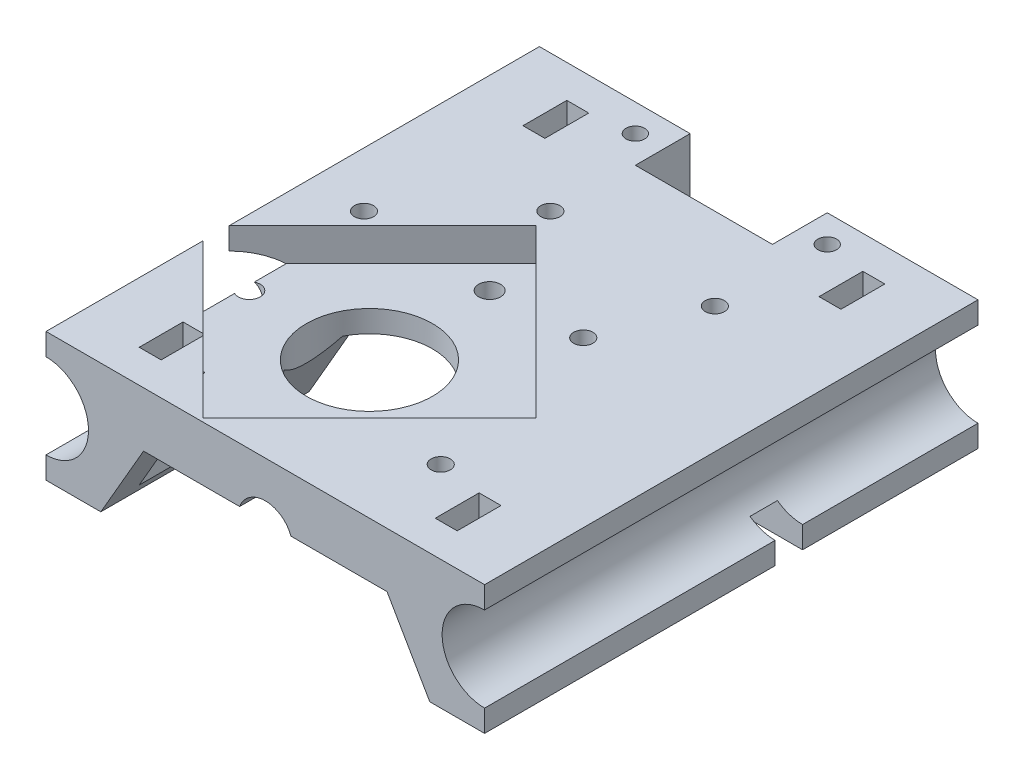
SolidWorks part; units mm, degrees
material "ABS"
ref_plane "Plano frontal" through (0, 0, 0) normal (0, 0, 1) x (1, 0, 0)
ref_plane "Plano superior" through (0, 0, 0) normal (0, 1, 0) x (1, 0, 0)
ref_plane "Plano direito" through (0, 0, 0) normal (1, 0, 0) x (0, 0, -1)
sketch "Esboço1" plane through (0, 0, 0) normal (0, 0, 1) x (1, 0, 0)
  line L0 (40, 0) -> (-40, 0)
  line L1 (-40, -19.5) -> (-40, -23.5)
  line L2 (-40, -23.5) -> (-30, -23.5)
  line L3 (-30, -23.5) -> (-22.2058, -10)
  line L4 (-22.2058, -10) -> (-4.6837, -10)
  line L5 (-40, 0) -> (-40, -4)
  line L6 (0, 0) -> (0, -46.1263) construction
  line L7 (40, 0) -> (40, -4)
  line L8 (30, -23.5) -> (22.2058, -10)
  line L9 (40, -23.5) -> (30, -23.5)
  line L10 (40, -19.5) -> (40, -23.5)
  line L11 (4.6837, -10) -> (22.2058, -10)
  line L12 (-40, -11.75) -> (40, -11.75) construction
  arc A0 (-40, -4) -> (-40, -19.5) centre (-40, -11.75) cw
  arc A1 (40, -4) -> (40, -19.5) centre (40, -11.75) ccw
  arc A2 (4.6837, -10) -> (-4.6837, -10) centre (0, -11.75) ccw
  point P17 (0, -12.2866)
  point P21 (0, 0)
  dimension "D1" = 7.75
  dimension "D7" = 5
  dimension "D2" = 4
  dimension "D3" = 60
  dimension "D4" = 10
  dimension "D5" = 10
  dimension "D6" = 40
extrude "Ressalto-extrusão1" add sketch "Esboço1" along normal blind 90
sketch "Esboço2" plane through (0, 0, 0) normal (0, 1, 0) x (1, 0, 0)
  line L1 (-42.4056, -59) -> (-12, -28.5944)
  line L2 (-42.4056, -59) -> (-12, -89.4056)
  line L3 (-12, -89.4056) -> (18.4056, -59)
  line L4 (-12, -28.5944) -> (18.4056, -59)
  line L5 (-42.4056, -59) -> (18.4056, -59) construction
  line L6 (-12, -89.4056) -> (-12, -28.5944) construction
  line L8 (-40, -90) -> (-40, 0) construction
  line L9 (40, -90) -> (-40, -90) construction
  line L11 (-22.2058, -90) -> (-4.6837, -90) construction
  circle A0 centre (-12, -59) radius 5
  point P0 (-12, -59)
  dimension "D4" = 10
  dimension "D1" = 43
  dimension "D2" = 28
  dimension "D3" = 31
extrude "Corte-extrusão1" cut sketch "Esboço2" against normal offset from surface (6 mm away) 4 up to face at (-13.4448, -10, 45)
sketch "Esboço3" plane through (0, -6, 0) normal (0, 1, 0) x (1, 0, 0)
  line L2 (-6.7523, -61.9088) -> (5.6269, -39.576) construction
  line L3 (-17.6288, -61.0776) -> (-25.3093, -40.2687) construction
  line L4 (-12, -37.0797) -> (9.9203, -59) construction
  line L5 (-12, -37.0797) -> (-33.9203, -59) construction
  line L6 (-33.9203, -59) -> (-12, -80.9203) construction
  line L7 (9.9203, -59) -> (-12, -80.9203) construction
  line L8 (-12, -37.0797) -> (-12, -80.9203) construction
  line L9 (-33.9203, -59) -> (9.9203, -59) construction
  line L10 (40, -90) -> (-40, -90) construction
  line L13 (-12, -28.5944) -> (-40, -56.5944) construction
  line L14 (4.6837, -90) -> (22.2058, -90) construction
  line L16 (-12.5, -10) -> (12.5, -10)
  line L17 (-12.5, -10) -> (-12.5, 0)
  line L18 (-12.5, 0) -> (12.5, 0)
  line L19 (12.5, -10) -> (12.5, 0)
  line L20 (-12.5, -10) -> (12.5, 0) construction
  line L21 (-12.5, 0) -> (12.5, -10) construction
  line L22 (0, -12.8859) -> (0, -1.9558) construction
  line L24 (18.4056, -59) -> (-12, -28.5944) construction
  circle A0 centre (-12, -37.0797) radius 2
  circle A1 centre (9.9203, -59) radius 2
  circle A2 centre (-12, -80.9203) radius 2
  circle A3 centre (-33.9203, -59) radius 2
  circle A4 centre (-12, -59) radius 11.5
  arc A5 (-17.6288, -61.0776) -> (-6.7523, -61.9088) centre (-12, -59) ccw construction
  circle A6 centre (-30, -42) radius 1.75
  circle A7 centre (10, -42) radius 1.75
  circle A8 centre (10, -42) radius 5 construction
  circle A9 centre (-30, -42) radius 5 construction
  circle A10 centre (-17.5, -5) radius 1.7
  circle A11 centre (17.5, -5) radius 1.7
  circle A12 centre (17, -75) radius 1.75
  circle A13 centre (-13, -25) radius 1.75
  circle A14 centre (17, -25) radius 1.75
  circle A15 centre (17, -25) radius 7.5 construction
  circle A16 centre (-13, -25) radius 7.5 construction
  circle A17 centre (17, -75) radius 7.5 construction
  point P0 (-11.5, -62)
  point P5 (0, 0)
  point P6 (-12, -59)
  point P29 (0, 0)
  point P38 (0, -5)
  point P60 (17, -75)
  point P66 (12.5, -5)
  dimension "D3" = 23
  dimension "D4" = 12
  dimension "D5" = 3.5
  dimension "D8" = 10
  dimension "D12" = 3.4
  dimension "D13" = 3.5
  dimension "D17" = 15
  dimension "D19" = 4
  dimension "D2" = 31
  dimension "D6" = 48
  dimension "D7" = 40
  dimension "D9" = 10
  dimension "D10" = 25
  dimension "D11" = 17.5
  dimension "D14" = 15
  dimension "D15" = 30
  dimension "D16" = 50
  dimension "D18" = 22
  dimension "D20" = 17
  dimension "D21" = 31
  dimension "D22" = 7
  dimension "D23" = 17
extrude "Corte-extrusão2" cut sketch "Esboço3" against normal through all and the other way through all
sketch "Esboço4" plane through (0, -10, 0) normal (0, -1, 0) x (1, 0, 0)
  line L0 (-44.5112, 37) -> (44.1077, 37)
  line L2 (-44.5112, 37) -> (-44.5112, 32)
  line L3 (-44.5112, 32) -> (44.1077, 32)
  line L4 (44.1077, 32) -> (44.1077, 37)
  circle A0 centre (-30, 42) radius 5 construction
  circle A1 centre (10, 42) radius 5 construction
  point P11 (-28.4465, 37.2475)
  dimension "D1" = 10
  dimension "D2" = 5
extrude "Corte-extrusão4" cut sketch "Esboço4" against normal blind 12 from offset 20
sketch "Esboço6" plane through (0, -23.5, 0) normal (0, -1, 0) x (1, 0, 0)
  line L0 (-40, 90) -> (-40, 37) construction
  line L2 (-20, 32) -> (-40, 32)
  line L5 (-20, 32) -> (-20, 52)
  line L6 (-20, 52) -> (-40, 52)
  line L7 (-40, 32) -> (-40, 52)
  line L8 (-20, 32) -> (-40, 52) construction
  line L9 (-20, 52) -> (-40, 32) construction
  line L10 (-30, 32) -> (-40, 32) construction
  circle A0 centre (17, 75) radius 8
  circle A1 centre (17, 25) radius 8
  circle A2 centre (-13, 25) radius 8
  point P0 (-30, 42)
  dimension "D1" = 16
extrude "Corte-extrusão7" cut sketch "Esboço6" against normal up to surface (13.5 mm away) up to face at (-14, -10, 80.9203)
sketch "Esboço7" plane through (0, 0, 0) normal (0, 1, 0) x (1, 0, 0)
  line L0 (-32.25, 0) -> (-32.25, -90) construction
  line L1 (40, -90) -> (-40, -90) construction
  line L3 (32.25, -90) -> (32.25, 0) construction
  line L5 (27.0009, -70) -> (27.0009, -90) construction
  line L6 (40, -90) -> (-40, -90) construction
  line L7 (44.8347, -45) -> (-53.0929, -45) construction
  line L8 (25.0009, -76) -> (29.0009, -76)
  line L9 (25.0009, -76) -> (25.0009, -84)
  line L10 (25.0009, -84) -> (29.0009, -84)
  line L11 (29.0009, -76) -> (29.0009, -84)
  line L12 (25.0009, -76) -> (29.0009, -84) construction
  line L13 (25.0009, -84) -> (29.0009, -76) construction
  line L14 (25.0009, -6) -> (29.0009, -14) construction
  line L15 (25.0009, -14) -> (29.0009, -6) construction
  line L16 (27.0009, -20) -> (27.0009, 0) construction
  line L17 (29.0009, -14) -> (29.0009, -6)
  line L18 (25.0009, -6) -> (29.0009, -6)
  line L19 (25.0009, -14) -> (25.0009, -6)
  line L20 (25.0009, -14) -> (29.0009, -14)
  line L21 (0, 4.9721) -> (0, -101.7412) construction
  line L22 (-27.0009, -20) -> (-27.0009, 0) construction
  line L23 (-25.0009, -14) -> (-29.0009, -6) construction
  line L24 (-25.0009, -6) -> (-29.0009, -14) construction
  line L25 (-25.0009, -84) -> (-29.0009, -76) construction
  line L26 (-25.0009, -76) -> (-29.0009, -84) construction
  line L27 (-27.0009, -70) -> (-27.0009, -90) construction
  line L28 (-25.0009, -14) -> (-29.0009, -14)
  line L29 (-25.0009, -14) -> (-25.0009, -6)
  line L30 (-25.0009, -6) -> (-29.0009, -6)
  line L31 (-29.0009, -14) -> (-29.0009, -6)
  line L32 (-29.0009, -76) -> (-29.0009, -84)
  line L33 (-25.0009, -84) -> (-29.0009, -84)
  line L34 (-25.0009, -76) -> (-25.0009, -84)
  line L35 (-25.0009, -76) -> (-29.0009, -76)
  point P10 (27.0009, -80)
  point P27 (27.0009, -10)
  point P43 (-27.0009, -10)
  point P44 (-27.0009, -80)
  dimension "D1" = 20
  dimension "D2" = 8
  dimension "D3" = 4
extrude "Corte-extrusão8" cut sketch "Esboço7" against normal through all
sketch "Esboço11" plane through (0, -10, 0) normal (0, -1, 0) x (1, 0, 0)
  circle A0 centre (-13, 25) radius 3.5
  circle A1 centre (-13, 25) radius 1.75
  circle A2 centre (17, 25) radius 1.75
  circle A3 centre (17, 25) radius 3.5
  circle A4 centre (17, 75) radius 3.5
  circle A5 centre (17, 75) radius 1.75
  dimension "D1" = 7
extrude "Ressalto-extrusão3" add sketch "Esboço11" along normal blind 12
